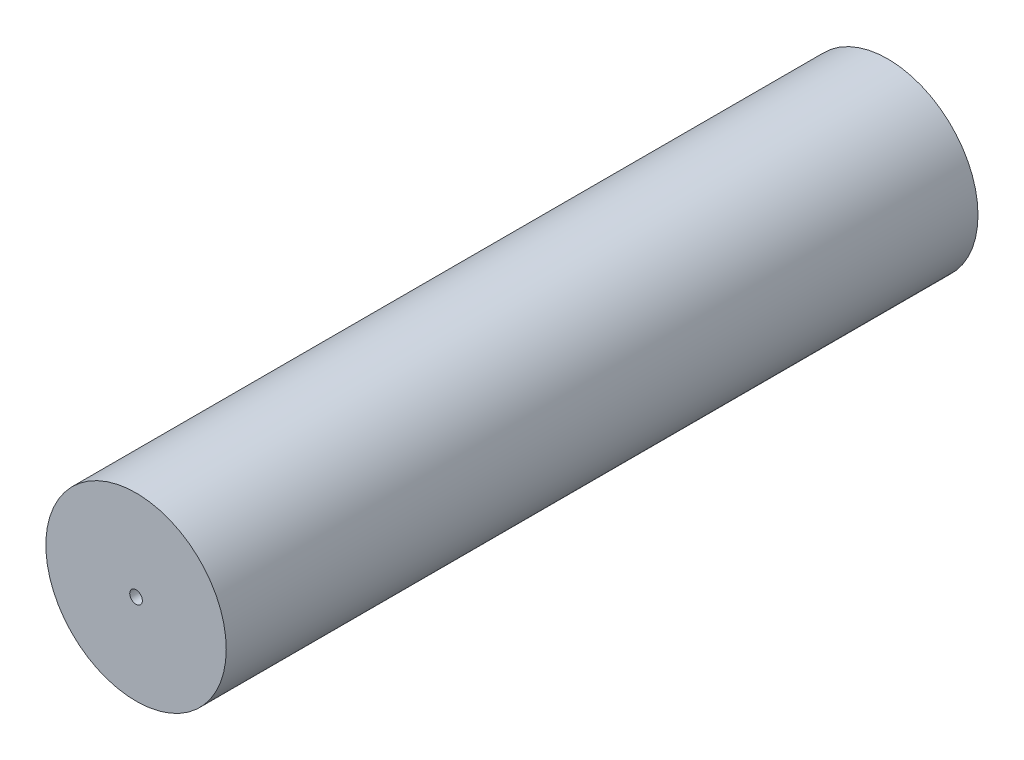
SolidWorks part; units mm, degrees
ref_plane "前视基准面" through (0, 0, 0) normal (0, 0, 1) x (1, 0, 0)
ref_plane "上视基准面" through (0, 0, 0) normal (0, 1, 0) x (1, 0, 0)
ref_plane "右视基准面" through (0, 0, 0) normal (1, 0, 0) x (0, 0, -1)
other "Configuration Table"
sketch "草图1" plane through (0, 0, 0) normal (0, 0, 1) x (1, 0, 0)
  circle A0 centre (0, 0) radius 30
  dimension "D1" = 60
extrude "凸台-拉伸1" add sketch "草图1" along normal blind 250
sketch "草图2" plane through (0, 0, 250) normal (0, 0, 1) x (1, 0, 0)
  circle A0 centre (0, 0) radius 2.1
  dimension "D1" = 4.2
extrude "切除-拉伸1" cut sketch "草图2" against normal blind 250
